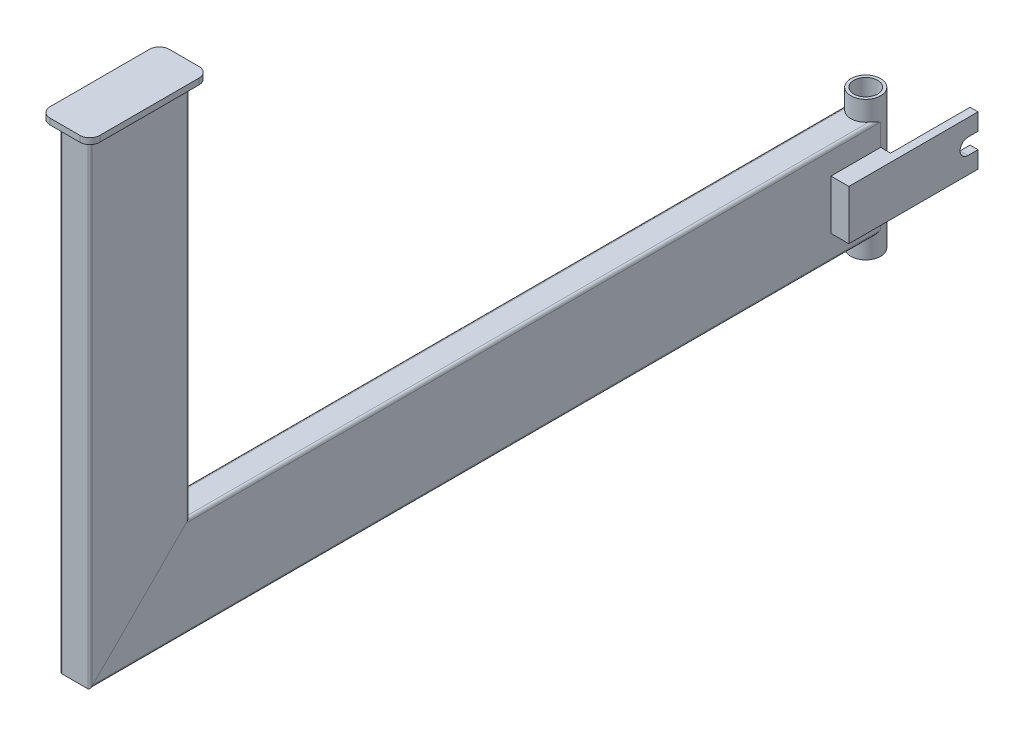
SolidWorks part; units mm, degrees
material "Structural Steel"
ref_plane "Piano frontale" through (0, 0, 0) normal (0, 0, 1) x (1, 0, 0)
ref_plane "Piano superiore" through (0, 0, 0) normal (0, 1, 0) x (1, 0, 0)
ref_plane "Piano destro" through (0, 0, 0) normal (1, 0, 0) x (0, 0, -1)
sketch "Schizzo1" plane through (0, 0, 0) normal (0, 0, 1) x (1, 0, 0)
  line L1 (3, 0) -> (27, 0)
  line L2 (0, 3) -> (0, 97)
  line L3 (3, 100) -> (27, 100)
  line L4 (30, 3) -> (30, 97)
  arc A0 (3, 0) -> (0, 3) centre (3, 3) cw
  arc A1 (27, 0) -> (30, 3) centre (27, 3) ccw
  arc A2 (27, 100) -> (30, 97) centre (27, 97) cw
  arc A3 (0, 97) -> (3, 100) centre (3, 97) cw
  point P7 (0, 0)
  point P10 (30, 0)
  point P15 (0, 100)
  dimension "D3" = 3
  dimension "D1" = 30
  dimension "D2" = 100
extrude "Estrusione-Sottile1" add sketch "Schizzo1" along normal blind 796 thin
sketch "Schizzo2" plane through (30, 0, 0) normal (1, 0, 0) x (0, 0, -1)
  line L0 (-796, 100) -> (-696, 100)
  line L1 (-796, 100) -> (0, 100) construction
  line L2 (-696, 100) -> (-796, 0)
  line L3 (-796, 0) -> (-796, 100)
  dimension "D1" = 45
extrude "Taglio-Estrusione1" cut sketch "Schizzo2" against normal through all
sketch "Schizzo3" plane through (0, 100, 0) normal (0, 1, 0) x (1, 0, 0)
  line L0 (27, 0) -> (3, 0) construction
  circle A0 centre (15, 0) radius 15
  dimension "D1" = 30
extrude "Estrusione-Estrusione1" add sketch "Schizzo3" along normal blind 20 and the other way blind 120
sketch "Schizzo4" plane through (0, 120, 0) normal (0, 1, 0) x (1, 0, 0)
  circle A0 centre (15, 0) radius 12
  dimension "D1" = 24
extrude "Taglio-Estrusione2" cut sketch "Schizzo4" against normal through all
sketch "Schizzo5" plane through (30, 0, 0) normal (1, 0, 0) x (0, 0, -1)
  line L0 (0, 3) -> (0, 97) construction
  line L1 (0, 75) -> (-50, 75)
  line L2 (0, 75) -> (0, 25)
  line L3 (0, 25) -> (-50, 25)
  line L4 (-50, 75) -> (-50, 25)
  line L5 (-696, 100) -> (-9, 100) construction
  dimension "D1" = 50
  dimension "D2" = 25
  dimension "D3" = 50
extrude "Estrusione-Estrusione2" add sketch "Schizzo5" along normal blind 10
sketch "Schizzo6" plane through (40, 0, 0) normal (1, 0, 0) x (0, 0, -1)
  line L0 (-1050, 50) -> (48950, 50) construction
  line L1 (-50, 75) -> (80, 75)
  line L2 (-50, 75) -> (-50, 25)
  line L3 (-50, 25) -> (80, 25)
  line L4 (80, 75) -> (80, 58)
  line L5 (70, 58) -> (80, 58)
  line L6 (70, 42) -> (80, 42)
  line L7 (80, 42) -> (80, 25)
  arc A0 (70, 58) -> (70, 42) centre (70, 50) ccw
  point P8 (-50, 50)
  dimension "D3" = 16
  dimension "D1" = 50
  dimension "D2" = 130
  dimension "D4" = 10
extrude "Estrusione-Estrusione3" add sketch "Schizzo6" along normal blind 8
ref_plane "Piano1" through (15, 0, 0) normal (1, 0, 0) x (0, 0, -1)
sketch "Schizzo7" plane through (15, 0, 0) normal (1, 0, 0) x (0, 0, -1)
  line L0 (-746, 50) -> (-746, 474.5139) construction
  line L1 (-793, 3) -> (-699, 97) construction
  line L2 (-796, 488.5) -> (-696, 488.5)
  line L3 (-696, 100) -> (-696, 488.5)
  line L4 (-796, 488.5) -> (-796, 0)
  line L5 (-796, 0) -> (-696, 100)
  point P7 (-746, 488.5)
  dimension "D1" = 488.5
extrude "Estrusione-Estrusione4" add sketch "Schizzo7" along normal mid plane 30 separate body
fillet "Raccordo1" radius 2 4 edges at (30, 294.25, 696) (30, 244.25, 796) (0, 244.25, 796) (0, 294.25, 696)
sketch "Schizzo8" plane through (0, 488.5, 0) normal (0, 1, 0) x (1, 0, 0)
  line L0 (30, -698) -> (30, -794) construction
  line L1 (3, -793) -> (27, -793)
  line L2 (3, -793) -> (3, -699)
  line L3 (3, -699) -> (27, -699)
  line L4 (27, -793) -> (27, -699)
  line L5 (3, -793) -> (27, -699) construction
  line L6 (3, -699) -> (27, -793) construction
  line L7 (0, -698) -> (0, -794) construction
  line L8 (28, -696) -> (2, -696) construction
  line L9 (28, -796) -> (2, -796) construction
  point P0 (15, -746)
  dimension "D1" = 3
  dimension "D2" = 3
  dimension "D3" = 3
  dimension "D4" = 3
extrude "Taglio-Estrusione3" cut sketch "Schizzo8" against normal through all both and the other way through all
sketch "Schizzo9" plane through (0, 488.5, 0) normal (0, 1, 0) x (1, 0, 0)
  line L0 (30, -698) -> (30, -794) construction
  line L1 (0, -806) -> (30, -806)
  line L2 (-10, -796) -> (-10, -696)
  line L3 (0, -686) -> (30, -686)
  line L4 (40, -796) -> (40, -696)
  line L5 (-10, -806) -> (40, -686) construction
  line L6 (-10, -686) -> (40, -806) construction
  line L7 (28, -696) -> (2, -696) construction
  arc A0 (30, -806) -> (40, -796) centre (30, -796) ccw
  arc A1 (0, -806) -> (-10, -796) centre (0, -796) cw
  arc A2 (-10, -696) -> (0, -686) centre (0, -696) cw
  arc A3 (30, -686) -> (40, -696) centre (30, -696) cw
  point P0 (15, -746)
  point P7 (30, -746)
  point P8 (40, -746)
  point P11 (15, -696)
  point P12 (15, -686)
  dimension "D3" = 10
  dimension "D1" = 50
  dimension "D2" = 120
extrude "Estrusione-Estrusione5" add sketch "Schizzo9" against normal blind 6
ref_plane "Piano2" through (0, 50, 0) normal (0, -1, 0) x (-1, 0, 0)
equation "\"j3\"=13.8349"
